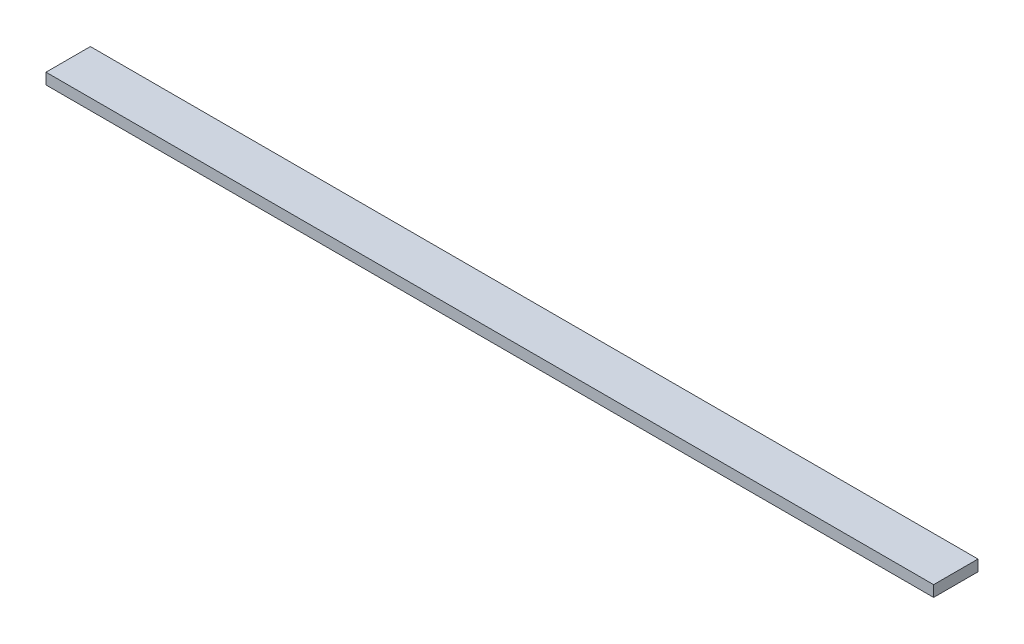
SolidWorks part; units mm, degrees
material "6061-T6 (SS)"
ref_plane "Front Plane" through (0, 0, 0) normal (0, 0, 1) x (1, 0, 0)
ref_plane "Top Plane" through (0, 0, 0) normal (0, 1, 0) x (1, 0, 0)
ref_plane "Right Plane" through (0, 0, 0) normal (1, 0, 0) x (0, 0, -1)
sketch "Sketch1" plane through (0, 0, 0) normal (0, 1, 0) x (1, 0, 0)
  line L1 (-254, 12.7) -> (254, 12.7)
  line L2 (-254, 12.7) -> (-254, -12.7)
  line L3 (-254, -12.7) -> (254, -12.7)
  line L4 (254, 12.7) -> (254, -12.7)
  line L5 (-254, 12.7) -> (254, -12.7) construction
  line L6 (-254, -12.7) -> (254, 12.7) construction
  point P0 (0, 0)
  dimension "D1" = 25.4
  dimension "D2" = 508
extrude "Boss-Extrude1" add sketch "Sketch1" along normal blind 6.35
